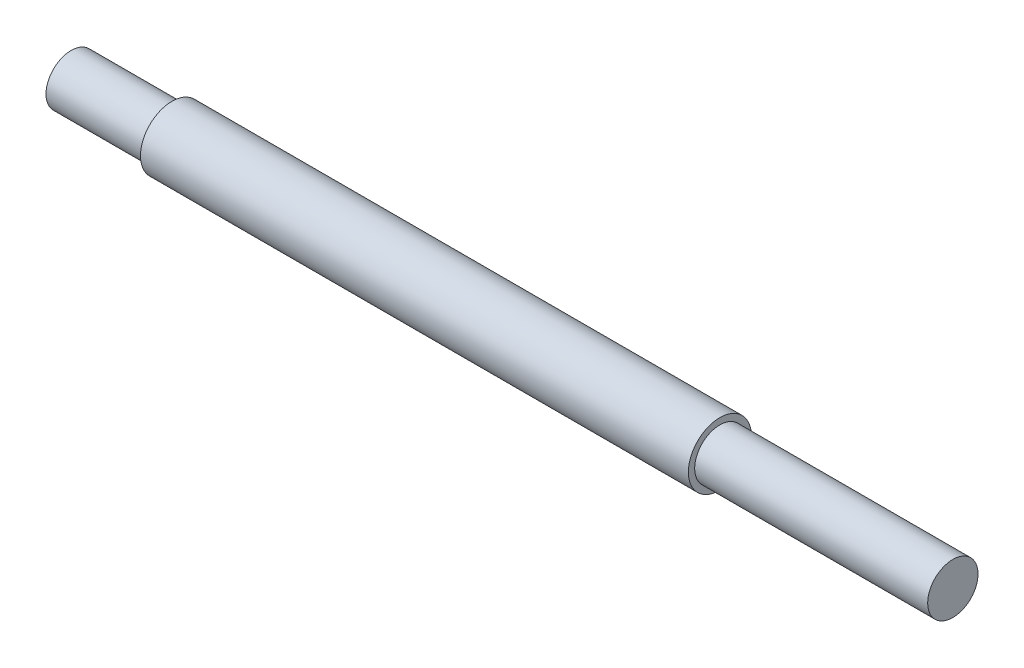
SolidWorks part; units mm, degrees
ref_plane "Front Plane" through (0, 0, 0) normal (0, 0, 1) x (1, 0, 0)
ref_plane "Top Plane" through (0, 0, 0) normal (0, 1, 0) x (1, 0, 0)
ref_plane "Right Plane" through (0, 0, 0) normal (1, 0, 0) x (0, 0, -1)
sketch "Sketch1" plane through (0, 0, 0) normal (0, 1, 0) x (1, 0, 0)
  line L0 (0, 0) -> (35, 0)
  line L1 (35, 0) -> (35, 1)
  line L2 (35, 1) -> (25.75, 1)
  line L3 (25.75, 1) -> (25.75, 1.25)
  line L4 (25.75, 1.25) -> (4, 1.25)
  line L5 (4, 1.25) -> (4, 1)
  line L6 (4, 1) -> (0, 1)
  line L7 (0, 1) -> (0, 0)
  dimension "D1" = 1
  dimension "D2" = 35
  dimension "D3" = 1
  dimension "D4" = 9.25
  dimension "D5" = 4
  dimension "D6" = 0.25
revolve "Revolve1" add sketch "Sketch1" angle 360 about L0
